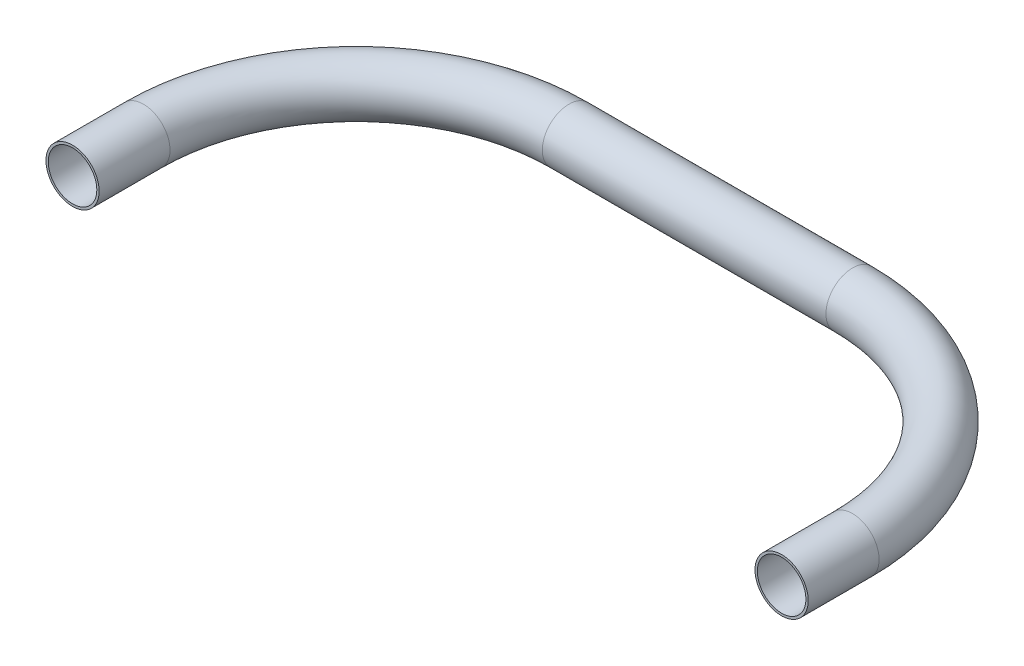
SolidWorks part; units mm, degrees
ref_plane "Front Plane" through (0, 0, 0) normal (0, 0, 1) x (1, 0, 0)
ref_plane "Top Plane" through (0, 0, 0) normal (0, 1, 0) x (1, 0, 0)
ref_plane "Right Plane" through (0, 0, 0) normal (1, 0, 0) x (0, 0, -1)
sketch "Sketch1" plane through (0, 0, 0) normal (0, 1, 0) x (1, 0, 0)
  line L0 (0, 0) -> (0, 50.8)
  line L1 (-152.4, 203.2) -> (-355.6, 203.2)
  line L2 (-508, 50.8) -> (-508, 0)
  arc A0 (0, 50.8) -> (-152.4, 203.2) centre (-152.4, 50.8) ccw
  arc A1 (-355.6, 203.2) -> (-508, 50.8) centre (-355.6, 50.8) ccw
  point P6 (0, 203.2)
  point P10 (-508, 203.2)
  dimension "D3" = 152.4
  dimension "D5" = 152.4
  dimension "D1" = 203.2
  dimension "D2" = 508
  dimension "D4" = 203.2
sketch "Sketch4" plane through (0, 0, 0) normal (0, 0, 1) x (1, 0, 0)
  circle A0 centre (-508, 0) radius 19.05
  circle A1 centre (-508, 0) radius 17.399
  dimension "D1" = 1.651
  dimension "D2" = 38.1
sweep "Sweep1" add profiles "Sketch4" path "Sketch1"
